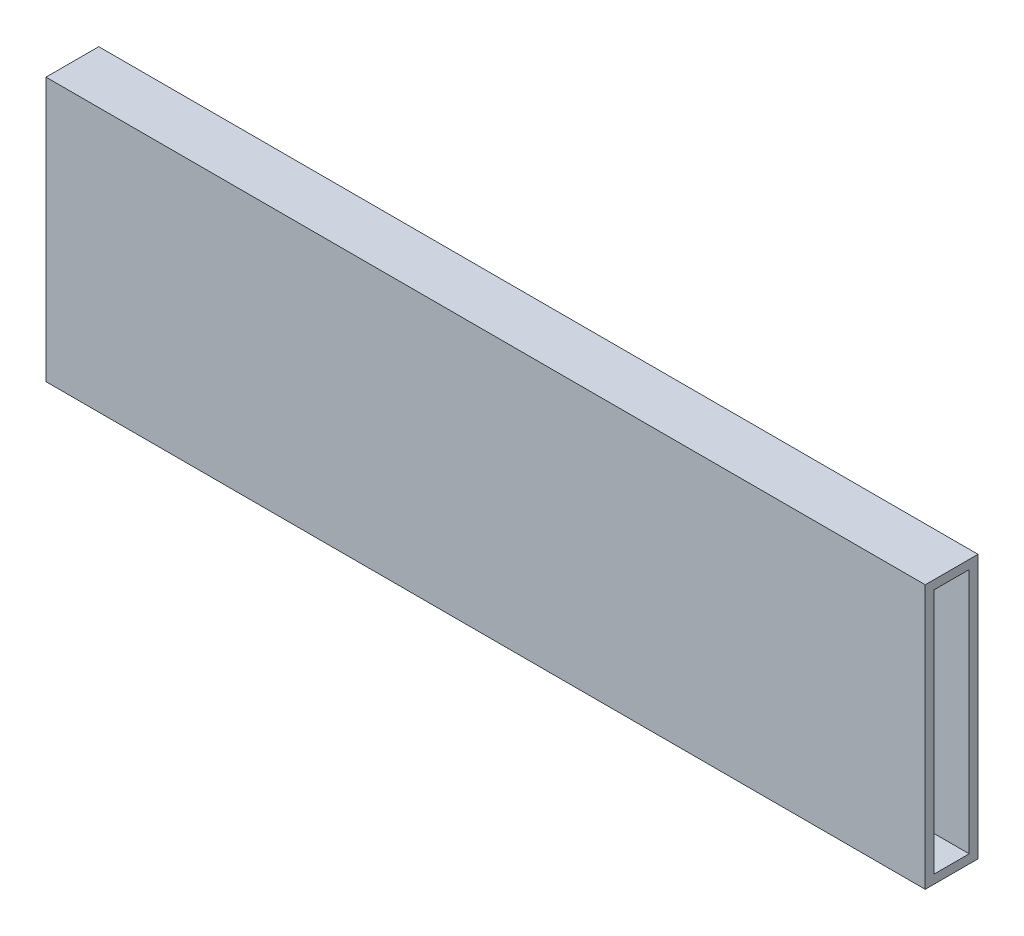
SolidWorks part; units mm, degrees
ref_plane "Płaszczyzna przednia" through (0, 0, 0) normal (0, 0, 1) x (1, 0, 0)
ref_plane "Płaszczyzna górna" through (0, 0, 0) normal (0, 1, 0) x (1, 0, 0)
ref_plane "Płaszczyzna prawa" through (0, 0, 0) normal (1, 0, 0) x (0, 0, -1)
sketch "Szkic1" plane through (0, 0, 0) normal (0, 0, 1) x (1, 0, 0)
  line L1 (-27.6006, 15.6988) -> (72.3994, 15.6988)
  line L2 (-27.6006, 15.6988) -> (-27.6006, -14.3012)
  line L3 (-27.6006, -14.3012) -> (72.3994, -14.3012)
  line L4 (72.3994, 15.6988) -> (72.3994, -14.3012)
  dimension "D1" = 30
  dimension "D2" = 100
extrude "Dodanie-wyciągnięcie1" add sketch "Szkic1" along normal blind 6
sketch "Szkic2" plane through (72.3994, 0, 0) normal (1, 0, 0) x (0, 0, -1)
  line L0 (0, -14.3012) -> (0, 15.6988) construction
  line L1 (-1, 14.6988) -> (-5, 14.6988)
  line L2 (-1, 14.6988) -> (-1, -13.3012)
  line L3 (-1, -13.3012) -> (-5, -13.3012)
  line L4 (-5, 14.6988) -> (-5, -13.3012)
  line L5 (-6, -14.3012) -> (0, -14.3012) construction
  line L6 (-6, 15.6988) -> (0, 15.6988) construction
  line L7 (-6, -14.3012) -> (-6, 15.6988) construction
  point P8 (-3, -14.3012)
  dimension "D1" = 1
  dimension "D2" = 1
  dimension "D3" = 1
  dimension "D4" = 1
extrude "Wytnij-wyciągnięcie1" cut sketch "Szkic2" against normal through all
